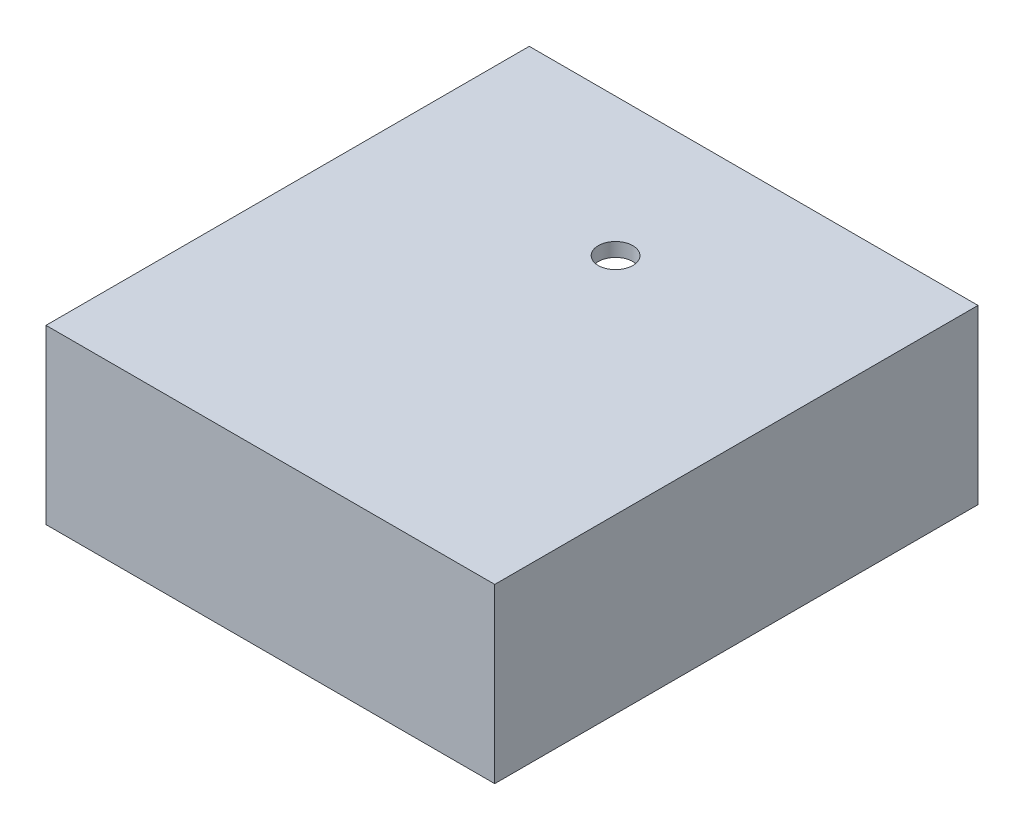
SolidWorks part; units mm, degrees
ref_plane "Front Plane" through (0, 0, 0) normal (0, 0, 1) x (1, 0, 0)
ref_plane "Top Plane" through (0, 0, 0) normal (0, 1, 0) x (1, 0, 0)
ref_plane "Right Plane" through (0, 0, 0) normal (1, 0, 0) x (0, 0, -1)
sketch "Sketch1" plane through (0, 0, 0) normal (0, 1, 0) x (1, 0, 0)
  line L1 (0, 0) -> (65, 0)
  line L2 (0, 0) -> (0, -70)
  line L3 (0, -70) -> (65, -70)
  line L4 (65, 0) -> (65, -70)
  dimension "D1" = 65
  dimension "D2" = 70
extrude "Boss-Extrude1" add sketch "Sketch1" along normal blind 25
sketch "Sketch8" plane through (0, 0, 0) normal (0, 0, -1) x (-1, 0, 0)
  line L0 (-32.5, 25) -> (-32.5, 0) construction
  line L1 (-65, 25) -> (0, 25) construction
  line L2 (-65, 0) -> (0, 0) construction
  line L4 (-63, 2) -> (-2, 2)
  line L5 (-63, 2) -> (-63, 23)
  line L6 (-63, 23) -> (-2, 23)
  line L7 (-2, 2) -> (-2, 23)
  line L8 (-63, 2) -> (-2, 23) construction
  line L9 (-63, 23) -> (-2, 2) construction
  point P6 (-32.5, 12.5)
  dimension "D1" = 21
  dimension "D2" = 61
extrude "Cut-Extrude1" cut sketch "Sketch8" against normal blind 40
sketch "Sketch9" plane through (0, 25, 0) normal (0, 1, 0) x (1, 0, 0)
  line L0 (32.5, 0) -> (32.5, -20) construction
  line L2 (65, 0) -> (0, 0) construction
  circle A1 centre (32.5, -20) radius 2.5
extrude "Cut-Extrude2" cut sketch "Sketch9" against normal blind 30
